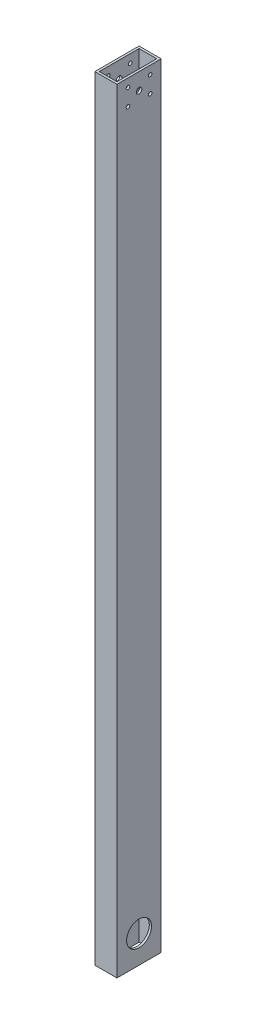
SolidWorks part; units mm, degrees
ref_plane "Front Plane" through (0, 0, 0) normal (0, 0, 1) x (1, 0, 0)
ref_plane "Top Plane" through (0, 0, 0) normal (0, 1, 0) x (1, 0, 0)
ref_plane "Right Plane" through (0, 0, 0) normal (1, 0, 0) x (0, 0, -1)
sketch3d "3DSketch1"
  line L0 (0, 0, 0) -> (0, 889, 0)
  dimension "D1" = 889
other "Versaframe VERSAFRAME 2 X 1 X 0.1 (1)"
ref_plane "Plane1" through (0, 0, 0) normal (0, 1, 0) x (1, 0, 0)
sketch "Sketch1" plane through (0, 0, 0) normal (0, 1, 0) x (1, 0, 0)
  line L0 (-10.16, 22.86) -> (-10.16, -22.86)
  line L1 (-12.7, 25.4) -> (12.7, 25.4)
  line L2 (-12.7, 25.4) -> (-12.7, -25.4)
  line L3 (-12.7, -25.4) -> (12.7, -25.4)
  line L4 (12.7, 25.4) -> (12.7, -25.4)
  line L5 (-12.7, 25.4) -> (12.7, -25.4) construction
  line L6 (-12.7, -25.4) -> (12.7, 25.4) construction
  line L7 (-10.16, -22.86) -> (10.16, -22.86)
  line L8 (10.16, 22.86) -> (10.16, -22.86)
  line L9 (-10.16, 22.86) -> (10.16, 22.86)
  line L10 (0, 25.4) -> (0, -25.4) construction
  line L12 (12.7, 0) -> (-12.7, 0) construction
  point P0 (0, 0)
  point P12 (0, 22.86)
  point P15 (-10.16, 0)
  point P16 (10.16, 0)
  point P17 (0, -22.86)
  point P18 (0, 0)
  dimension "D1" = 25.4
  dimension "D2" = 50.8
  dimension "D3" = 2.54
sketch "Sketch2" plane through (12.7, 0, 0) normal (1, 0, 0) x (0, 0, -1)
  circle A0 centre (0, 31.75) radius 14.2875
  dimension "D1" = 28.575
  dimension "D2" = 31.75
extrude "Cut-Extrude1" cut sketch "Sketch2" against normal through all both and the other way through all
sketch "Sketch3" plane through (12.7, 0, 0) normal (1, 0, 0) x (0, 0, -1)
  circle A0 centre (-12.7, 879.475) radius 2.07 construction
  circle A1 centre (-12.7, 860.425) radius 2.07 construction
  circle A2 centre (0, 869.95) radius 3.175 construction
  circle A3 centre (12.7, 860.425) radius 2.07 construction
  circle A4 centre (12.7, 879.475) radius 2.07 construction
  circle A5 centre (-12.7, 879.475) radius 2.07
  circle A6 centre (-12.7, 860.425) radius 2.07
  circle A7 centre (0, 869.95) radius 3.175
  circle A8 centre (12.7, 860.425) radius 2.07
  circle A9 centre (12.7, 879.475) radius 2.07
extrude "Cut-Extrude2" cut sketch "Sketch3" against normal through all both and the other way through all
equation "\"Length\"= 35"
equation "\"D1@3DSketch1\"=\"Length\""
